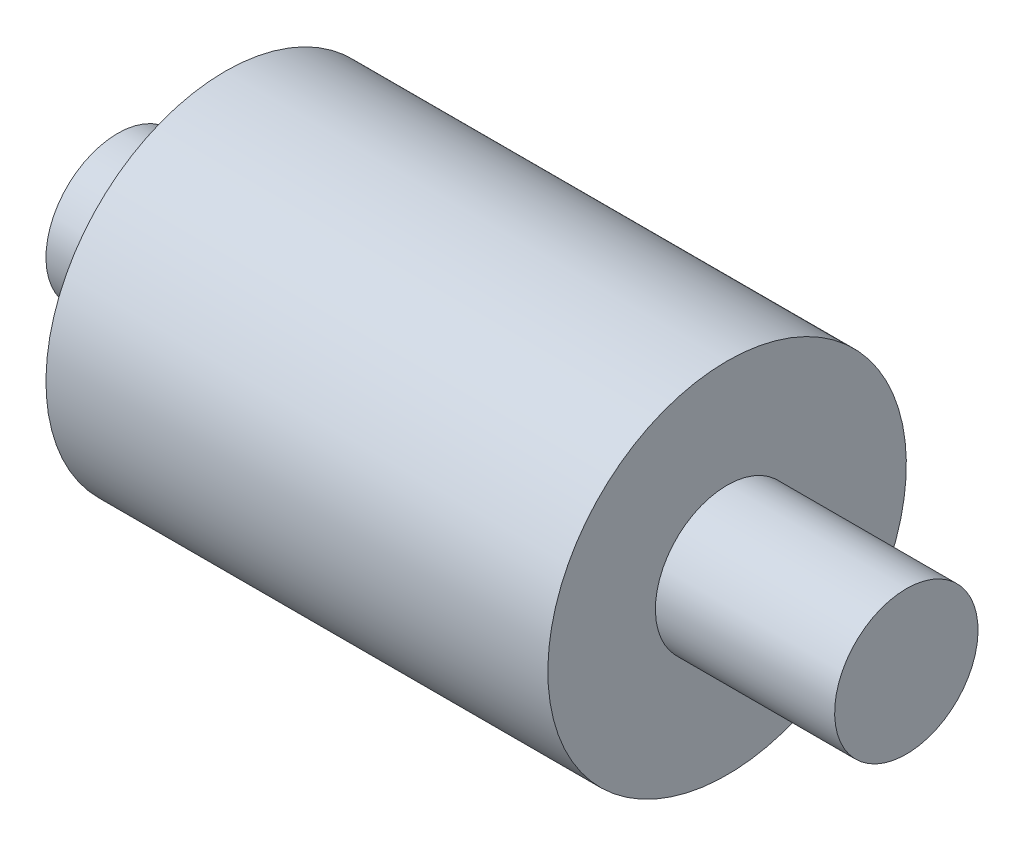
SolidWorks part; units mm, degrees
ref_plane "Piano frontale" through (0, 0, 0) normal (0, 0, 1) x (1, 0, 0)
ref_plane "Piano superiore" through (0, 0, 0) normal (0, 1, 0) x (1, 0, 0)
ref_plane "Piano destro" through (0, 0, 0) normal (1, 0, 0) x (0, 0, -1)
sketch "Schizzo1" plane through (0, 0, 0) normal (0, 0, 1) x (1, 0, 0)
  line L0 (-38.2911, 0) -> (-35.2911, 0)
  line L1 (-35.2911, 0) -> (-35.2911, 3)
  line L2 (-35.2911, 3) -> (-21.2911, 3)
  line L3 (-21.2911, 3) -> (-21.2911, 0)
  line L4 (-21.2911, 0) -> (-16.2911, 0)
  line L5 (-16.2911, 0) -> (-16.2911, -2)
  line L6 (-16.2911, -2) -> (-38.2911, -2)
  line L7 (-38.2911, -2) -> (-38.2911, 0)
  dimension "D1" = 3
  dimension "D2" = 2
  dimension "D3" = 3
  dimension "D4" = 14
  dimension "D5" = 5
revolve "Rivoluzione1" add sketch "Schizzo1" angle 360 about L6
